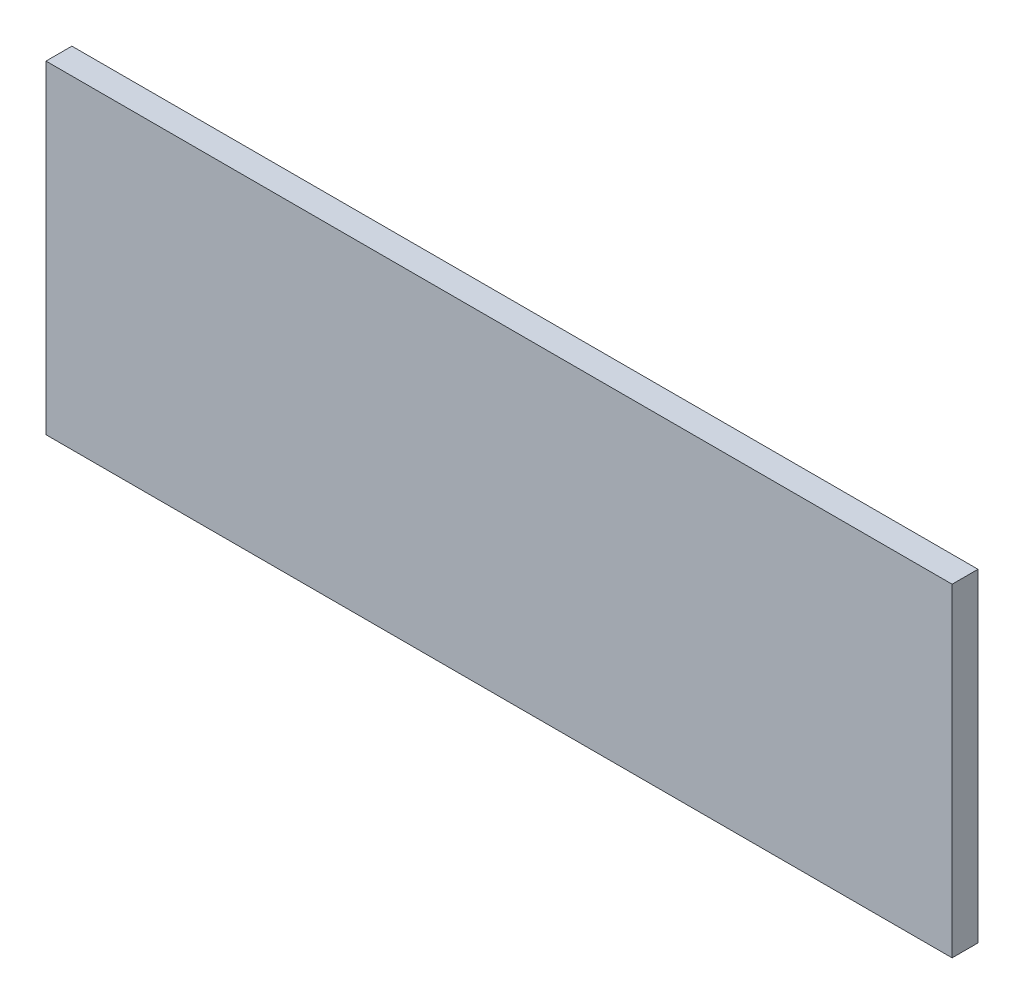
SolidWorks part; units mm, degrees
ref_plane "前视" through (0, 0, 0) normal (0, 0, 1) x (1, 0, 0)
ref_plane "上视" through (0, 0, 0) normal (0, 1, 0) x (1, 0, 0)
ref_plane "右视" through (0, 0, 0) normal (1, 0, 0) x (0, 0, -1)
sketch "草图1" plane through (0, 0, 0) normal (0, 0, 1) x (1, 0, 0)
  line L0 (0, -309.0802) -> (0, 309.0802) construction
  line L1 (-350, -125) -> (350, -125)
  line L2 (-350, -125) -> (-350, 125)
  line L3 (-350, 125) -> (350, 125)
  line L4 (350, -125) -> (350, 125)
  line L5 (-416.575, 0) -> (416.575, 0) construction
  line L6 (-60, 231.9077) -> (-60, -177.8082) construction
  line L7 (-405.3499, 80) -> (106.7949, 80) construction
  line L8 (-300, 281.0174) -> (-300, -177.8082) construction
  line L9 (-140, 189.8136) -> (-140, -190.9976) construction
  line L10 (-220, 297.8551) -> (-220, -190.9976) construction
  dimension "D1" = 700
  dimension "D2" = 250
  dimension "D3" = 80
  dimension "D4" = 50
  dimension "D5" = 80
  dimension "D7" = 80
  dimension "D8" = 80
extrude "基体-拉伸" add sketch "草图1" along normal blind 20
